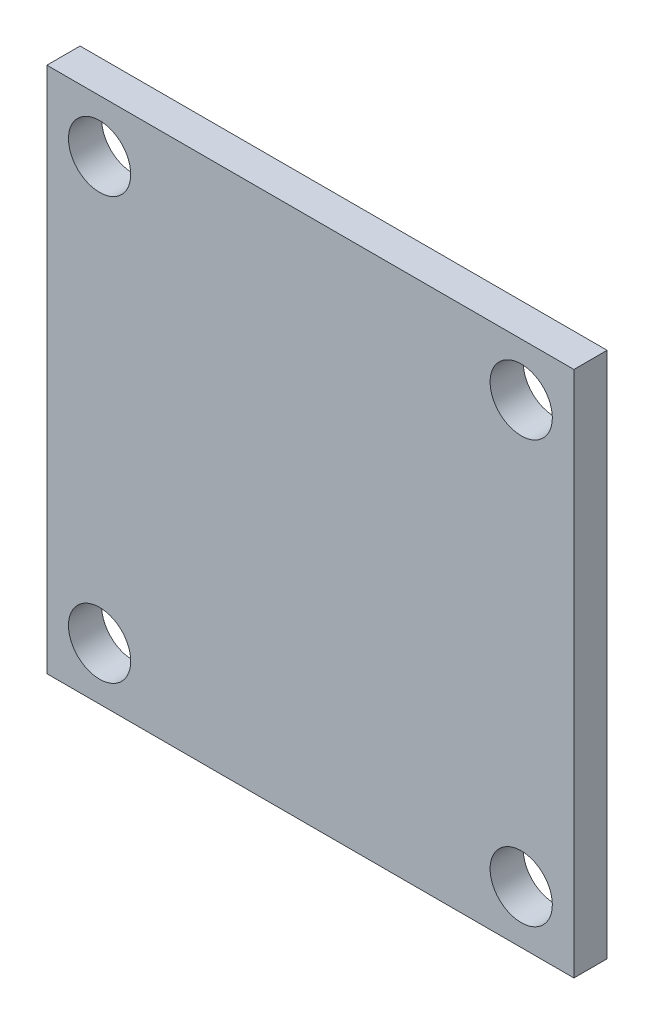
SolidWorks part; units mm, degrees
ref_plane "Front Plane" through (0, 0, 0) normal (0, 0, 1) x (1, 0, 0)
ref_plane "Top Plane" through (0, 0, 0) normal (0, 1, 0) x (1, 0, 0)
ref_plane "Right Plane" through (0, 0, 0) normal (1, 0, 0) x (0, 0, -1)
sketch "Sketch1" plane through (0, 0, 0) normal (0, 0, 1) x (1, 0, 0)
  line L1 (-12.7, 12.7) -> (12.7, 12.7)
  line L2 (-12.7, 12.7) -> (-12.7, -12.7)
  line L3 (-12.7, -12.7) -> (12.7, -12.7)
  line L4 (12.7, 12.7) -> (12.7, -12.7)
  circle A0 centre (-10.16, 10.16) radius 1.5
  circle A1 centre (10.16, 10.16) radius 1.5
  circle A2 centre (10.16, -10.16) radius 1.5
  circle A3 centre (-10.16, -10.16) radius 1.5
  point P4 (12.7, 0)
  point P6 (0, 12.7)
  point P15 (0, 0)
  point P16 (0, 0)
  point P17 (0, 0)
  point P18 (0, 0)
  point P19 (4.7576, 4.5211)
  point P20 (-5.5088, -8.7501)
  dimension "D7" = 3
  dimension "D1" = 25.4
  dimension "D2" = 25.4
  dimension "D3" = 2.54
  dimension "D4" = 2.54
  dimension "D5" = 2.54
  dimension "D6" = 2.54
extrude "Boss-Extrude1" add sketch "Sketch1" along normal blind 1.6
